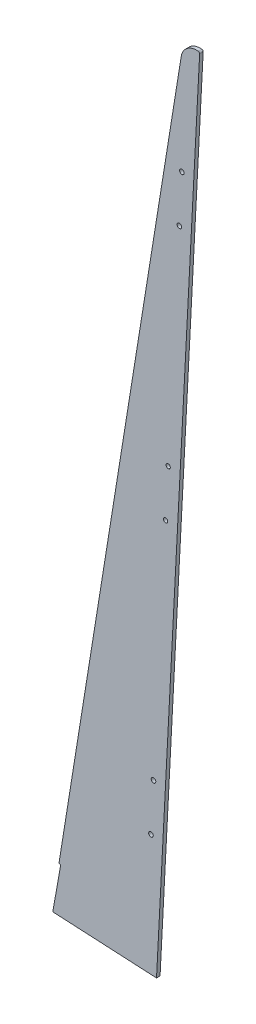
SolidWorks part; units mm, degrees
material "Acrylic (Medium-high impact)"
ref_plane "Front Plane" through (0, 0, 0) normal (0, 0, 1) x (1, 0, 0)
ref_plane "Top Plane" through (0, 0, 0) normal (0, 1, 0) x (1, 0, 0)
ref_plane "Right Plane" through (0, 0, 0) normal (1, 0, 0) x (0, 0, -1)
sketch "Sketch1" plane through (0, 0, 0) normal (0, 0, 1) x (1, 0, 0)
  line L0 (0, 0) -> (148, 0)
  line L1 (148, 0) -> (210.7107, 1195)
  line L2 (210.7107, 1195) -> (0, 0)
  dimension "D1" = 148
  dimension "D2" = 1195
  dimension "D3" = 80
extrude "Boss-Extrude1" add sketch "Sketch1" along normal blind 5
fillet "Fillet1" radius 2 1 edges at (210.7107, 1195, 2.5)
sketch "Sketch2" plane through (0, 0, 5) normal (0, 0, 1) x (1, 0, 0)
  line L0 (191.9423, 1088.5589) -> (174.2158, 1091.6845)
  line L1 (205.0293, 1162.7787) -> (0, 0) construction
  line L2 (174.2158, 1091.6845) -> (10.3184, 72.9153)
  line L3 (10.3184, 72.9153) -> (12.7804, 72.4812)
  line L4 (12.7804, 72.4812) -> (191.9423, 1088.5589)
  dimension "D1" = 2.5
  dimension "D2" = 18
extrude "Boss-Extrude2" add sketch "Sketch2" against normal up to surface (5 mm away) up to face at (140.5595, 581.7428, 0)
sketch "Sketch3" plane through (0, 0, 5) normal (0, 0, 1) x (1, 0, 0)
  line L0 (174.2158, 1091.6845) -> (182.9556, 1146.0106)
  line L1 (174.2158, 1091.6845) -> (10.3184, 72.9153) construction
  line L2 (174.2158, 1091.6845) -> (191.9423, 1088.5589)
  line L3 (191.9423, 1088.5589) -> (205.0293, 1162.7787)
  line L11 (148, 0) -> (208.9961, 1162.3266)
  line L12 (205.0293, 1162.7787) -> (191.9423, 1088.5589)
  line L13 (191.9423, 1088.5589) -> (174.2158, 1091.6845)
  line L14 (174.2158, 1091.6845) -> (10.3184, 72.9153)
  line L15 (10.3184, 72.9153) -> (12.7804, 72.4812)
  line L16 (12.7804, 72.4812) -> (0, 0)
  line L17 (0, 0) -> (148, 0)
  arc A0 (182.9556, 1146.0106) -> (207.2253, 1164.4185) centre (204.7282, 1142.5078) cw
  arc A1 (208.9961, 1162.3266) -> (205.0293, 1162.7787) centre (206.9989, 1162.4314) ccw construction
  arc A3 (208.9961, 1162.3266) -> (205.0293, 1162.7787) centre (206.9989, 1162.4314) ccw
  arc A4 (207.2253, 1164.4185) -> (205.0293, 1162.7787) centre (206.9989, 1162.4314) ccw
  dimension "D1" = 0
extrude "Boss-Extrude3" add sketch "Sketch3" against normal up to surface (5 mm away) up to face at (118.9369, 581.5764, 0)
sketch "Sketch4" plane through (0, 0, 5) normal (0, 0, 1) x (1, 0, 0)
  line L0 (0, 0) -> (2.1126, 11.9813)
  line L1 (2.1126, 11.9813) -> (148.0883, 1.6828)
  line L2 (148.0883, 1.6828) -> (148, 0)
  line L3 (148, 0) -> (0, 0)
  line L4 (148, 0) -> (208.9961, 1162.3266) construction
  line L5 (12.7804, 72.4812) -> (0, 0) construction
  point P3 (0, 0)
  point P4 (0, 0)
  point P9 (0, 0)
  point P10 (0, 0)
  point P11 (0, 0)
  point P12 (0, 0)
  point P14 (0, 0)
  point P17 (0, 0)
  point P18 (0, 0)
  dimension "D1" = 1.6851
  dimension "D2" = 12.1662
extrude "Boss-Extrude4" add sketch "Sketch4" against normal up to surface (5 mm away) up to face at (109.5717, 517.6238, 0)
sketch "Sketch5" plane through (0, 0, 5) normal (0, 0, 1) x (1, 0, 0)
  line L0 (148.6793, 12.9442) -> (0.5454, 3.093)
  line L1 (148, 0) -> (208.9961, 1162.3266) construction
  line L2 (12.7804, 72.4812) -> (0, 0) construction
  line L3 (0.5454, 3.093) -> (0, 0)
  line L4 (0, 0) -> (148, 0)
  line L5 (0, 0) -> (148, 0) construction
  line L6 (148, 0) -> (148.6793, 12.9442)
  point P4 (0, 0)
  point P6 (0, 0)
  point P12 (0, 0)
  point P14 (0.5454, 3.093)
extrude "Cut-Extrude1" cut sketch "Sketch5" against normal through all
sketch "Sketch6" plane through (0, 0, 5) normal (0, 0, 1) x (1, 0, 0)
  circle A0 centre (180.3686, 937.5141) radius 3.25
  circle A1 centre (183.9322, 1005.4207) radius 3.25
  circle A2 centre (143.8328, 241.2966) radius 3.25
  circle A3 centre (140.2692, 173.3901) radius 3.25
  point P11 (0, 0)
  point P12 (0, 0)
  dimension "D1" = 6.5
extrude "Cut-Extrude2" cut sketch "Sketch6" against normal through all
sketch "Sketch7" plane through (0, 0, 5) normal (0, 0, 1) x (1, 0, 0)
  line L0 (148.6793, 12.9442) -> (148.0904, 1.7226)
  line L1 (148.6793, 12.9442) -> (208.9961, 1162.3266) construction
  line L2 (148.6793, 12.9442) -> (0.5454, 3.093) construction
  line L3 (148.0904, 1.7226) -> (54.1043, 6.6548)
  line L5 (148.6793, 12.9442) -> (54.1043, 6.6548)
  point P6 (148.0904, 1.7226)
  dimension "D1" = 11.237
extrude "Boss-Extrude5" add sketch "Sketch7" against normal up to surface (5 mm away) up to face at (187.1822, 1005.4207, 0)
sketch "Sketch8" plane through (0, 0, 5) normal (0, 0, 1) x (1, 0, 0)
  line L0 (54.1043, 6.6548) -> (1.6587, 9.407)
  line L1 (54.1043, 6.6548) -> (148.0904, 1.7226) construction
  line L2 (54.1043, 6.6548) -> (0.5454, 3.093) construction
  line L3 (12.7804, 72.4812) -> (0.5454, 3.093) construction
  line L4 (1.6587, 9.407) -> (0.5454, 3.093)
  line L5 (0.5454, 3.093) -> (54.1043, 6.6548)
extrude "Cut-Extrude3" cut sketch "Sketch8" against normal through all
sketch "Sketch9" plane through (0, 0, 5) normal (0, 0, 1) x (1, 0, 0)
  circle A0 centre (160.9682, 567.8257) radius 3
  circle A1 centre (164.5318, 635.7322) radius 3
  point P4 (0, 0)
  point P5 (0, 0)
  dimension "D1" = 6
extrude "Cut-Extrude4" cut sketch "Sketch9" against normal through all
